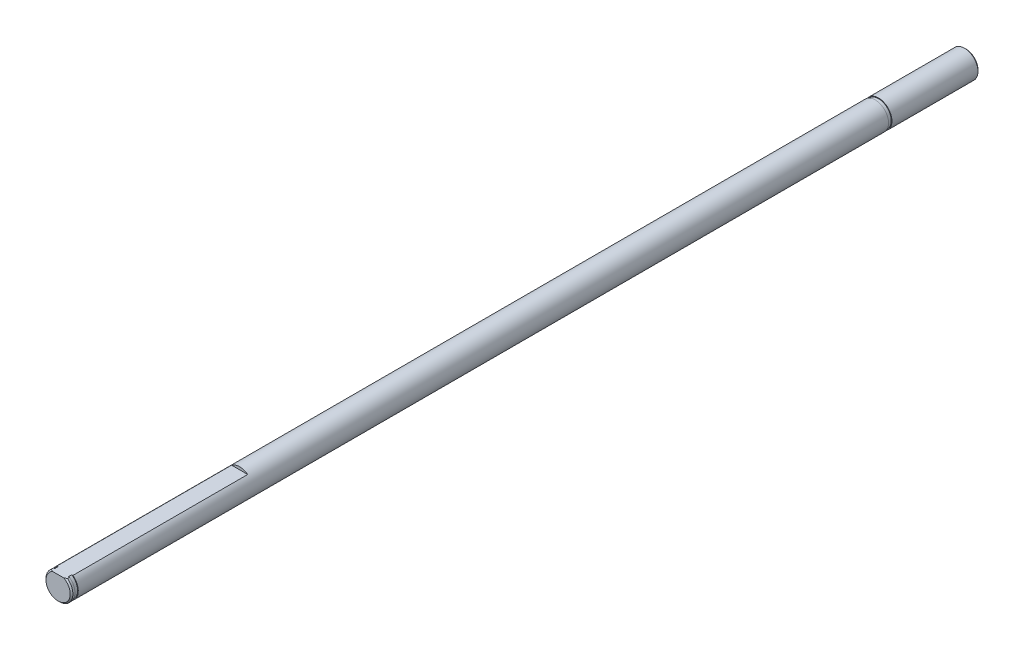
SolidWorks part; units mm, degrees
ref_plane "Vorne" through (0, 0, 0) normal (0, 0, 1) x (1, 0, 0)
ref_plane "Oben" through (0, 0, 0) normal (0, 1, 0) x (1, 0, 0)
ref_plane "Seite" through (0, 0, 0) normal (1, 0, 0) x (0, 0, -1)
sketch "Skizze1" plane through (0, 0, 0) normal (0, 0, 1) x (1, 0, 0)
  circle A0 centre (0, 0) radius 2
  point P3 (0, -3)
  dimension "D1" = 4
  dimension "D2" = 3
extrude "Aufsatz-Linear austragen1" add sketch "Skizze1" along normal mid plane 135
sketch "Skizze2" plane through (0, 0, 67.5) normal (0, 0, 1) x (1, 0, 0)
  point P0 (0, 0)
sketch "Skizze7" plane through (0, 0, 0) normal (1, 0, 0) x (0, 0, -1)
  line L0 (-67, 2) -> (-67, 1.9)
  line L1 (67.5, 2) -> (-67.5, 2) construction
  line L2 (-67, 1.9) -> (-66.5, 1.9)
  line L3 (-66.5, 1.9) -> (-66.5, 2)
  line L4 (-66.5, 2) -> (-67, 2)
  line L5 (54.5, 2) -> (54.5, 1.9)
  line L6 (54.5, 1.9) -> (54, 1.9)
  line L7 (54, 1.9) -> (54, 2)
  line L8 (54, 2) -> (54.5, 2)
  line L9 (-67.5, 2) -> (-67.5, -2) construction
  line L10 (67.5, 0) -> (-67.5, 0) construction
  line L11 (67.5, -2) -> (67.5, 2) construction
  dimension "D1" = 0.1
  dimension "D2" = 0.5
  dimension "D3" = 0.5
  dimension "D4" = 120.5
revolve "Schnitt-Rotation1" cut sketch "Skizze7" angle 360 about L10
sketch "Skizze8" plane through (0, 0, 67.5) normal (0, 0, 1) x (1, 0, 0)
  line L0 (1.2, 1.6) -> (-1.2, 1.6)
  line L1 (50, 0) -> (-50, 0) construction
  arc A0 (1.2, 1.6) -> (-1.2, 1.6) centre (0, 0) ccw
  circle A1 centre (0, 0) radius 2 construction
  dimension "D1" = 1.6
extrude "Schnitt-Linear austragen1" cut sketch "Skizze8" against normal blind 27
chamfer "Fase1" distance 0.2 angle 45 2 edges at (0, -2, 67.5) (2, 0, -67.5)
